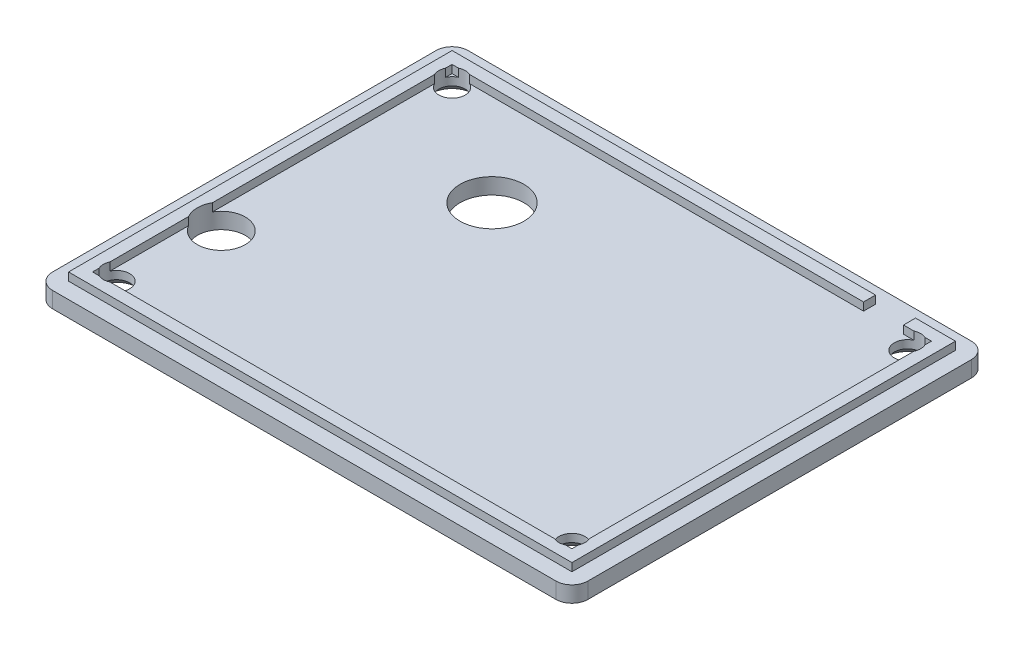
SolidWorks part; units mm, degrees
ref_plane "Спереди" through (0, 0, 0) normal (0, 0, 1) x (1, 0, 0)
ref_plane "Сверху" through (0, 0, 0) normal (0, 1, 0) x (1, 0, 0)
ref_plane "Справа" through (0, 0, 0) normal (1, 0, 0) x (0, 0, -1)
sketch "Эскиз1" plane through (0, 0, 0) normal (0, 1, 0) x (1, 0, 0)
  line L0 (0, 0) -> (-67, 0)
  line L1 (-67, 0) -> (-67, 52)
  line L2 (-67, 52) -> (0, 52)
  line L3 (0, 52) -> (0, 0)
  line L4 (-67, 0) -> (-65, 0)
  line L5 (-65, 0) -> (-65, 2)
  line L6 (-65, 2) -> (-65, 50)
  line L7 (-65, 50) -> (-2, 50)
  line L8 (-2, 50) -> (-2, 2)
  line L9 (-2, 2) -> (-65, 2)
  line L10 (-65, 2) -> (-65, 3.5)
  line L11 (-65, 3.5) -> (-63.5, 3.5)
  line L12 (-63.5, 3.5) -> (-63.5, 48.5)
  line L13 (-63.5, 48.5) -> (-3.5, 48.5)
  line L14 (-3.5, 48.5) -> (-3.5, 3.5)
  line L15 (-3.5, 3.5) -> (-63.5, 3.5)
extrude "Бобышка-Вытянуть1" add sketch "Эскиз1" along normal blind 2
sketch "Эскиз2" plane through (0, 2, 0) normal (0, 1, 0) x (1, 0, 0)
  line L0 (-63.5, 3.5) -> (-65, 3.5)
  line L1 (-65, 3.5) -> (-65, 2)
  line L2 (-65, 2) -> (-2, 2)
  line L3 (-2, 2) -> (-2, 50)
  line L4 (-2, 50) -> (-65, 50)
  line L5 (-65, 50) -> (-65, 3.5)
extrude "Бобышка-Вытянуть2" add sketch "Эскиз2" along normal blind 1
sketch "Эскиз3" plane through (0, 0, 0) normal (0, -1, 0) x (-1, 0, 0)
  line L0 (63.5, 48.5) -> (3.5, 48.5)
  line L1 (3.5, 48.5) -> (3.5, 3.5)
  line L2 (3.5, 3.5) -> (63.5, 3.5)
  line L3 (63.5, 3.5) -> (63.5, 48.5)
extrude "Бобышка-Вытянуть3" add sketch "Эскиз3" against normal blind 2
sketch "Эскиз4" plane through (0, 0, -50) normal (0, 0, -1) x (-1, 0, 0)
  line L0 (0, 2) -> (7, 2)
  line L1 (2, 2) -> (65, 2) construction
  line L2 (7, 2) -> (7, 3)
  line L3 (2, 3) -> (65, 3) construction
  line L4 (7, 3) -> (12, 3)
  line L5 (12, 3) -> (12, 2)
  line L6 (67, 2) -> (0, 2) construction
  line L7 (12, 2) -> (7, 2)
  line M1 (2, 2) -> (65, 2)
  line M3 (65, 3) -> (2, 3)
extrude "Вырез-Вытянуть1" cut sketch "Эскиз4" against normal blind 2 contours L5 L2 M3 M1
fillet "Скругление1" radius 2 4 edges at (0, 1, 0) (0, 1, -52) (-67, 1, -52) (-67, 1, 0)
sketch "Эскиз6" plane through (0, 0, 0) normal (0, -1, 0) x (-1, 0, 0)
  circle A0 centre (62, 47) radius 1.65
  circle A1 centre (62, 5) radius 1.65
  circle A2 centre (5, 47) radius 1.65
  circle A3 centre (5, 5) radius 1.65
extrude "Вырез-Вытянуть3" cut sketch "Эскиз6" against normal through all
chamfer "Фаска1" distance 1 angle 45 4 edges at (-5, 0, -6.65) (-5, 0, -45.35) (-62, 0, -3.35) (-62, 0, -48.65)
sketch "Эскиз7" plane through (0, 0, 0) normal (0, -1, 0) x (-1, 0, 0)
  line L0 (41, 37) -> (0, 37)
  line L3 (67, 37) -> (47.004, 37)
  line L4 (67, 12.0214) -> (60.8994, 12.0214)
  line L5 (67, 2) -> (67, 50) construction
  line L6 (60.8994, 12.0214) -> (60.8994, 17.0193)
  circle A0 centre (60.8994, 17.0193) radius 3
  circle A1 centre (47.004, 37) radius 4
  point P12 (60.4114, 15.0193)
extrude "Вырез-Вытянуть4" cut sketch "Эскиз7" against normal blind 10
